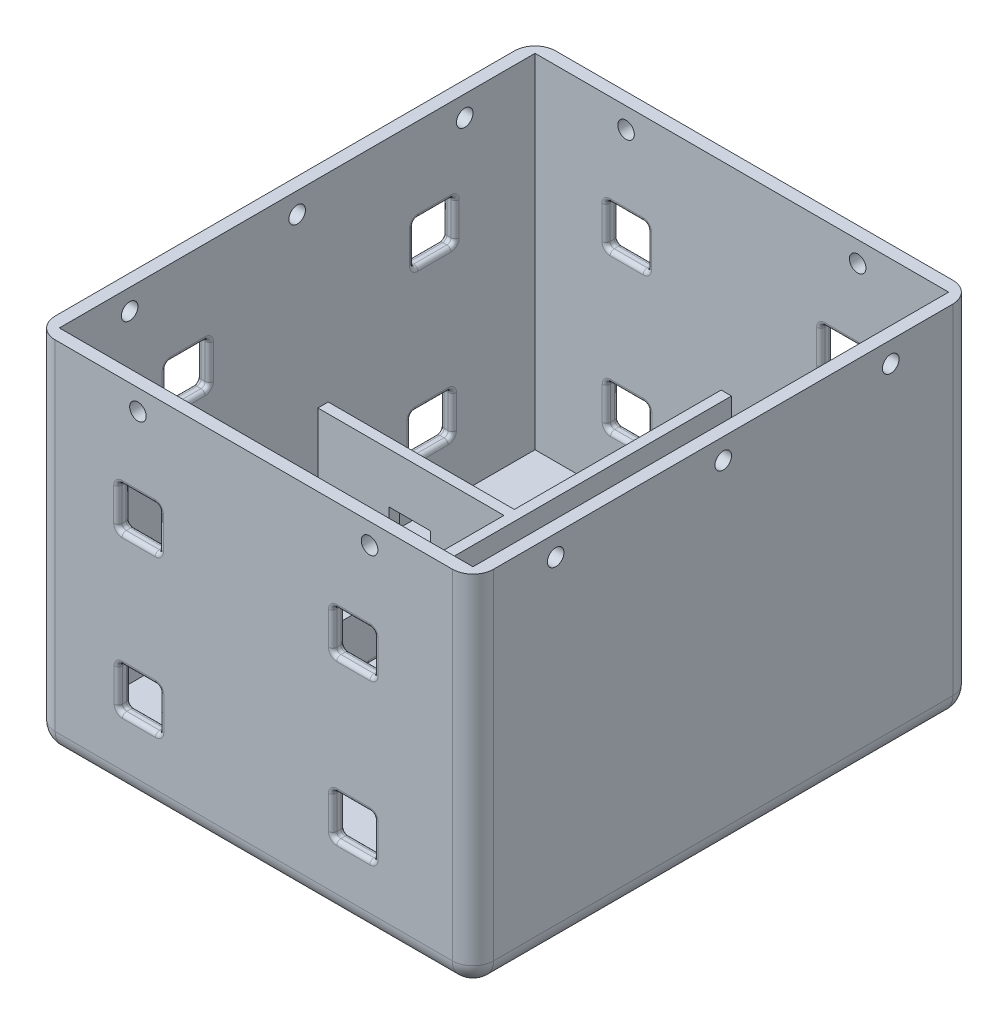
SolidWorks part; units mm, degrees
ref_plane "Front Plane" through (0, 0, 0) normal (0, 0, 1) x (1, 0, 0)
ref_plane "Top Plane" through (0, 0, 0) normal (0, 1, 0) x (1, 0, 0)
ref_plane "Right Plane" through (0, 0, 0) normal (1, 0, 0) x (0, 0, -1)
sketch "Sketch1" plane through (0, 0, 0) normal (0, 1, 0) x (1, 0, 0)
  line L1 (-50, 57.5) -> (50, 57.5)
  line L2 (-50, 57.5) -> (-50, -57.5)
  line L3 (-50, -57.5) -> (50, -57.5)
  line L4 (50, 57.5) -> (50, -57.5)
  line L5 (-50, 57.5) -> (50, -57.5) construction
  line L6 (-50, -57.5) -> (50, 57.5) construction
  line L7 (-53, 60.5) -> (53, 60.5)
  line L8 (-53, 60.5) -> (-53, -60.5)
  line L9 (-53, -60.5) -> (53, -60.5)
  line L10 (53, 60.5) -> (53, -60.5)
  line L11 (-53, 60.5) -> (53, -60.5) construction
  line L12 (-53, -60.5) -> (53, 60.5) construction
  point P0 (0, 0)
  point P6 (0, 0)
  dimension "D1" = 115
  dimension "D2" = 100
  dimension "D3" = 121
  dimension "D4" = 106
extrude "Boss-Extrude1" add sketch "Sketch1" along normal blind 83
sketch "Sketch2" plane through (0, 0, 0) normal (0, -1, 0) x (1, 0, 0)
  line L1 (-53, -60.5) -> (53, -60.5)
  line L2 (-53, -60.5) -> (-53, 60.5)
  line L3 (-53, 60.5) -> (53, 60.5)
  line L4 (53, -60.5) -> (53, 60.5)
extrude "Boss-Extrude2" add sketch "Sketch2" along normal blind 4
sketch "Sketch3" plane through (0, 0, 0) normal (0, 1, 0) x (1, 0, 0)
  line L0 (-5, 57.5) -> (-5, 7.5)
  line L1 (50, 57.5) -> (-50, 57.5) construction
  line L2 (-50, -57.5) -> (50, -57.5) construction
  line L3 (-5, 5) -> (-5, -57.5)
  line L4 (-5, 57.5) -> (-2.5, 57.5)
  line L5 (-2.5, 57.5) -> (-2.5, -57.5)
  line L6 (-50, -57.5) -> (50, -57.5) construction
  line L7 (-2.5, -57.5) -> (-5, -57.5)
  line L8 (-50, 57.5) -> (-50, -57.5) construction
  line L9 (-50, 7.5) -> (-5, 7.5)
  line L10 (-50, 57.5) -> (-50, -57.5) construction
  line L12 (-5, 5) -> (-50, 5)
  line L13 (-50, 5) -> (-50, 7.5)
  line L14 (50, 57.5) -> (-50, 57.5) construction
  dimension "D1" = 2.5
  dimension "D2" = 45
  dimension "D3" = 2.5
  dimension "D4" = 50
extrude "Boss-Extrude3" add sketch "Sketch3" along normal blind 35
sketch "Sketch6" plane through (0, 0, -5) normal (0, 0, 1) x (1, 0, 0)
  line L1 (-32.7488, 22.8733) -> (-22.7488, 22.8733)
  line L2 (-32.7488, 22.8733) -> (-32.7488, 12.8733)
  line L3 (-32.7488, 12.8733) -> (-22.7488, 12.8733)
  line L4 (-22.7488, 22.8733) -> (-22.7488, 12.8733)
  line L5 (-32.7488, 22.8733) -> (-22.7488, 12.8733) construction
  line L6 (-32.7488, 12.8733) -> (-22.7488, 22.8733) construction
  line L7 (19.0723, 22.1267) -> (29.0723, 22.1267)
  line L8 (19.0723, 22.1267) -> (19.0723, 12.1267)
  line L9 (19.0723, 12.1267) -> (29.0723, 12.1267)
  line L10 (29.0723, 22.1267) -> (29.0723, 12.1267)
  line L11 (19.0723, 22.1267) -> (29.0723, 12.1267) construction
  line L12 (19.0723, 12.1267) -> (29.0723, 22.1267) construction
  point P0 (-27.7488, 17.8733)
  point P5 (24.0723, 17.1267)
  dimension "D1" = 10
  dimension "D2" = 10
  dimension "D3" = 10
  dimension "D4" = 10
extrude "Cut-Extrude1" cut sketch "Sketch6" against normal blind 75 and the other way blind 92
sketch "Sketch7" plane through (-5, 0, 0) normal (-1, 0, 0) x (0, 0, 1)
  line L0 (-57.5, 35) -> (-7.5, 35) construction
  line L5 (21.25, 12.5) -> (31.25, 12.5)
  line L6 (21.25, 12.5) -> (21.25, 22.5)
  line L7 (-37.5, 12.5) -> (-27.5, 12.5)
  line L8 (-37.5, 12.5) -> (-37.5, 22.5)
  line L9 (-37.5, 22.5) -> (-27.5, 22.5)
  line L10 (-27.5, 12.5) -> (-27.5, 22.5)
  line L11 (-37.5, 12.5) -> (-27.5, 22.5) construction
  line L12 (-37.5, 22.5) -> (-27.5, 12.5) construction
  line L13 (21.25, 22.5) -> (31.25, 22.5)
  line L14 (31.25, 12.5) -> (31.25, 22.5)
  line L15 (21.25, 12.5) -> (31.25, 22.5) construction
  line L16 (21.25, 22.5) -> (31.25, 12.5) construction
  line L17 (-57.5, 35) -> (-57.5, 0) construction
  line L18 (57.5, 35) -> (57.5, 0) construction
  line L19 (-5, 35) -> (57.5, 35) construction
  point P0 (26.25, 17.5)
  point P5 (-32.5, 17.5)
  dimension "D1" = 10
  dimension "D2" = 10
  dimension "D3" = 10
  dimension "D4" = 10
  dimension "D5" = 17.5
  dimension "D6" = 25
  dimension "D7" = 31.25
  dimension "D8" = 17.5
extrude "Cut-Extrude2" cut sketch "Sketch7" along normal up to surface and the other way blind 8 up to face at (-53, 39.5, 0)
sketch "Sketch8" plane through (0, 0, 60.5) normal (0, 0, 1) x (1, 0, 0)
  line L0 (-50, 35) -> (-5, 35) construction
  line L1 (-32.85, 60.67) -> (-22.85, 60.67)
  line L2 (-32.85, 60.67) -> (-32.85, 50.67)
  line L3 (-32.85, 50.67) -> (-22.85, 50.67)
  line L4 (-22.85, 60.67) -> (-22.85, 50.67)
  line L5 (-5, 35) -> (-5, 0) construction
  dimension "D1" = 15.67
  dimension "D2" = 10
  dimension "D3" = 17.85
extrude "Cut-Extrude3" cut sketch "Sketch8" against normal blind 138
sketch "Sketch9" plane through (0, 0, 60.5) normal (0, 0, 1) x (1, 0, 0)
  line L1 (19.0723, 50.67) -> (29.0723, 50.67)
  line L2 (19.0723, 50.67) -> (19.0723, 60.67)
  line L3 (19.0723, 60.67) -> (29.0723, 60.67)
  line L4 (29.0723, 50.67) -> (29.0723, 60.67)
  dimension "D1" = 10
extrude "Cut-Extrude4" cut sketch "Sketch9" against normal blind 138
sketch "Sketch10" plane through (-53, 0, 0) normal (-1, 0, 0) x (0, 0, 1)
  line L0 (-57.5, 35) -> (-7.5, 35) construction
  line L1 (-38.18, 62.54) -> (-28.18, 62.54)
  line L2 (-38.18, 62.54) -> (-38.18, 52.54)
  line L3 (-38.18, 52.54) -> (-28.18, 52.54)
  line L4 (-28.18, 62.54) -> (-28.18, 52.54)
  line L5 (-38.18, 62.54) -> (-28.18, 52.54) construction
  line L6 (-38.18, 52.54) -> (-28.18, 62.54) construction
  line L7 (-57.5, 83) -> (-57.5, 0) construction
  line L9 (21.25, 52.17) -> (31.62, 52.17)
  line L10 (21.25, 52.17) -> (21.25, 62.54)
  line L11 (21.25, 62.54) -> (31.62, 62.54)
  line L12 (31.62, 52.17) -> (31.62, 62.54)
  point P0 (-33.18, 57.54)
  point P5 (-33.18, 52.54)
  dimension "D1" = 10
  dimension "D2" = 17.54
  dimension "D3" = 19.32
extrude "Cut-Extrude5" cut sketch "Sketch10" against normal blind 78
sketch "Sketch11" plane through (-53, 0, 0) normal (-1, 0, 0) x (0, 0, 1)
  line L0 (-60.5, 83) -> (-60.5, -4) construction
  line L1 (60.5, 83) -> (60.5, -4) construction
  line L2 (-60.5, 83) -> (60.5, 83) construction
  circle A0 centre (-40.5, 78) radius 2
  circle A1 centre (0, 78) radius 2
  circle A2 centre (40.5, 78) radius 2
  dimension "D1" = 20
  dimension "D2" = 40.5
  dimension "D3" = 20
  dimension "D4" = 5
  dimension "D5" = 5
  dimension "D6" = 5
extrude "Cut-Extrude6" cut sketch "Sketch11" against normal blind 132
sketch "Sketch12" plane through (0, 0, -60.5) normal (0, 0, -1) x (-1, 0, 0)
  line L0 (-53, 83) -> (-53, -4) construction
  line L1 (53, 83) -> (53, -4) construction
  line L2 (-53, 83) -> (53, 83) construction
  circle A0 centre (-28, 78) radius 2
  circle A1 centre (28, 78) radius 2
  dimension "D1" = 25
  dimension "D2" = 25
  dimension "D3" = 5
  dimension "D4" = 5
extrude "Cut-Extrude7" cut sketch "Sketch12" against normal blind 132
fillet "Fillet1" radius 5 4 edges at (53, 39.5, -60.5) (53, 39.5, 60.5) (-53, 39.5, 60.5) (-53, 39.5, -60.5)
fillet "Fillet2" radius 5 8 edges at (-51.5355, -4, 59.0355) (0, -4, 60.5) (51.5355, -4, 59.0355) (53, -4, 0) (51.5355, -4, -59.0355) (0, -4, -60.5) (-51.5355, -4, -59.0355) (-53, -4, 0)
fillet "Fillet4" radius 1 102 edges at (-2.5, 17.5, -37.5) (-2.5, 17.5, -27.5) (-5, 22.5, 26.25) (-5, 12.5, 26.25) (-2.5, 12.5, 26.25) (24.0723, 12.1267, -57.5) (24.0723, 22.1267, -60.5) (-27.7488, 22.8733, -57.5) (-27.7488, 12.8733, -57.5) (-27.7488, 12.8733, -60.5) (-27.7488, 22.8733, -60.5) (24.0723, 50.67, -57.5) (24.0723, 60.67, -57.5) (24.0723, 22.1267, 57.5) (24.0723, 12.1267, 60.5) (-27.7488, 22.8733, 57.5) (-27.7488, 12.8733, 57.5) (-27.7488, 12.8733, 60.5) (-27.7488, 22.8733, 60.5) (24.0723, 50.67, 57.5) (24.0723, 60.67, 60.5) (24.0723, 60.67, 57.5) (-27.85, 60.67, 57.5) (-27.85, 50.67, 60.5) (-50, 62.54, -33.18) (-53, 62.54, -33.18) (-53, 52.54, -33.18) (-50, 52.54, -33.18) (-50, 52.17, 26.435) (-53, 62.54, 26.435) (-50, 62.54, 26.435) (-53, 12.5, 26.25) (-50, 12.5, 26.25) (-50, 12.5, -32.5) (-53, 12.5, -32.5) (-50, 22.5, -32.5) (-5, 22.5, -32.5) (-3.75, 22.5, -37.5) (-5, 17.5, 21.25) (-3.75, 12.5, 21.25) (-5, 12.5, -32.5) (-3.75, 12.5, -37.5) (-3.75, 12.5, -27.5) (-5, 17.5, 31.25) (-3.75, 12.5, 31.25) (-2.5, 17.5, 31.25) (-3.75, 22.5, 31.25) (19.0723, 17.1267, -60.5) (29.0723, 17.1267, -60.5) (29.0723, 22.1267, -59) (-32.7488, 12.8733, -59) (-22.7488, 17.8733, -57.5) (-22.7488, 17.8733, -60.5) (-22.7488, 22.8733, -59) (-22.85, 55.67, -60.5) (-22.85, 60.67, -59) (-32.85, 55.67, -60.5) (-32.85, 50.67, -59) (-32.85, 55.67, -57.5) (19.0723, 60.67, -59) (19.0723, 55.67, -60.5) (19.0723, 50.67, -59) (19.0723, 55.67, -57.5) (29.0723, 50.67, -59) (29.0723, 55.67, -60.5) (29.0723, 55.67, -57.5) (19.0723, 17.1267, 57.5) (19.0723, 17.1267, 60.5) (-22.7488, 17.8733, 57.5) (-22.7488, 17.8733, 60.5) (-32.7488, 22.8733, 59) (29.0723, 55.67, 60.5) (29.0723, 50.67, 59) (29.0723, 55.67, 57.5) (19.0723, 50.67, 59) (19.0723, 55.67, 57.5) (-32.85, 50.67, 59) (-32.85, 55.67, 60.5) (-32.85, 55.67, 57.5) (-22.85, 50.67, 59) (-51.5, 52.54, -38.18) (-53, 57.54, -38.18) (-51.5, 62.54, -38.18) (-51.5, 62.54, -28.18) (-53, 57.54, -28.18) (-51.5, 52.54, -28.18) (-51.5, 62.54, 31.62) (-50, 57.355, 31.62) (-51.5, 62.54, 21.25) (-51.5, 12.5, 21.25) (-53, 17.5, 21.25) (-51.5, 22.5, 21.25) (-50, 17.5, 21.25) (-51.5, 22.5, 31.25) (-53, 17.5, 31.25) (-50, 17.5, 31.25) (-53, 17.5, -27.5) (-50, 17.5, -27.5) (-51.5, 12.5, -37.5) (-53, 17.5, -37.5) (-51.5, 22.5, -37.5) (-50, 17.5, -37.5)
